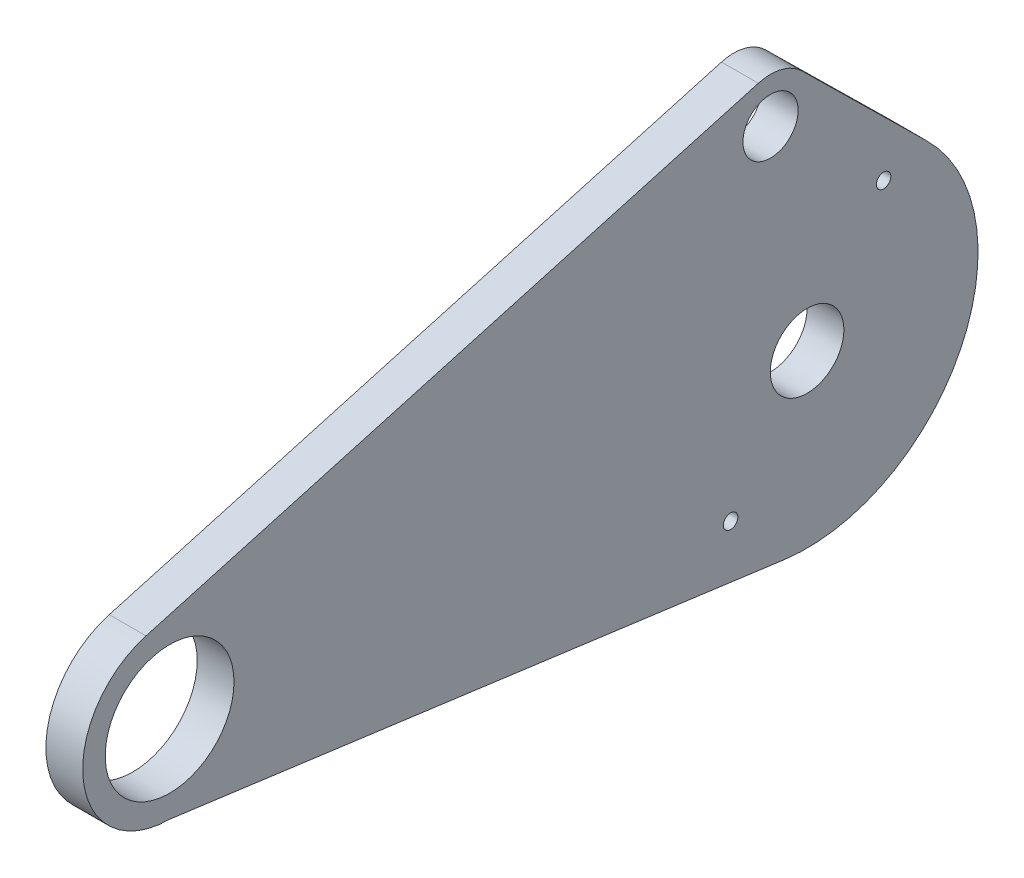
SolidWorks part; units mm, degrees
ref_plane "Front Plane" through (0, 0, 0) normal (0, 0, 1) x (1, 0, 0)
ref_plane "Top Plane" through (0, 0, 0) normal (0, 1, 0) x (1, 0, 0)
ref_plane "Right Plane" through (0, 0, 0) normal (1, 0, 0) x (0, 0, -1)
sketch "Sketch1" plane through (0, 0, 0) normal (1, 0, 0) x (0, 0, -1)
  line L4 (0, 15) -> (0, 11.1125) construction
  line L6 (0, 11.1125) -> (0, -11.1125) construction
  line L7 (0, -11.1125) -> (0, -15) construction
  line L8 (0, 15) -> (106.0756, 29.2378)
  line L9 (0, -15) -> (106.0756, -29.2378)
  line L10 (-4.0667, 14.4382) -> (101.5842, 44.1959)
  line L11 (130.6993, 21.0188) -> (109.1354, 42.2549)
  circle A0 centre (110, 0) radius 6.35
  circle A1 centre (0, 0) radius 11.1125
  arc A3 (106.0756, -29.2378) -> (106.0756, 29.2378) centre (110, 0) ccw
  arc A5 (0, 15) -> (0, -15) centre (0, 0) ccw
  arc A6 (106.0756, 29.2378) -> (106.0756, -29.2378) centre (110, 0) ccw construction
  arc A7 (0, -15) -> (0, 15) centre (0, 0) ccw construction
  circle A8 centre (0, 0) radius 110 construction
  circle A9 centre (0, 0) radius 100 construction
  circle A10 centre (103.6887, 36.7241) radius 4.7625
  circle A11 centre (103.6887, 36.7241) radius 7.7625
  dimension "D3" = 22.225
  dimension "D4" = 9.525
  dimension "D5" = 12.7
  dimension "D6" = 59
  dimension "D7" = 3
  dimension "D1" = 10
  dimension "D2" = 110
  dimension "D9" = 30
extrude "Boss-Extrude1" add sketch "Sketch1" along normal mid plane 6.35 contours A11 L8 A5 L9 A3 A0 A1 | A11 L10 A5 L8 | A11 L8 A3 L11 | A11 L8 A10 | L8 A11
hole_wizard "M3x0.5 Tapped Hole1" positions "Sketch2" profile "Sketch3" tap size "M3x0.5" standard "ANSI Metric" end condition through all
sketch "Sketch2" plane through (3.175, 0, 0) normal (1, 0, 0) x (0, 0, -1)
  line L0 (96.7991, -18.8528) -> (123.2009, 18.8528) construction
  line L2 (55, 0) -> (-55, 0) construction
  line L3 (0, 0) -> (110, 0) construction
  circle A1 centre (110, 0) radius 6.35 construction
  point P0 (123.2009, 18.8528)
  point P12 (110, 0)
  point P13 (96.7991, -18.8528)
  dimension "D1" = 23.015
  dimension "D2" = 125
sketch "Sketch3" plane through (3.175, 18.8528, -123.2009) normal (0, 1, 0) x (0, 0, -1)
  line L0 (0, 0) -> (0, 6.35)
  line L1 (0, 6.35) -> (1.25, 6.35)
  line L2 (1.25, 6.35) -> (1.25, 0)
  line L5 (1.25, 0) -> (0, 0)
  line L11 (0, -6.35) -> (0, 107.95) construction
  dimension "Thru Tap Drill Dia." = 2.5
  dimension "Thru Tap Drill Depth" = 6.35
cosmetic thread "Hole Thread1" parameters "D2"=3
cosmetic thread "Hole Thread2" parameters "D2"=3
hole_wizard "3/8 (0.3750) Dowel Hole1" positions "Sketch4" profile "Sketch5" hole size "3/8" standard "ANSI Inch"
sketch "Sketch4" plane through (3.175, 0, 0) normal (1, 0, 0) x (0, 0, -1)
  point P0 (65, 0)
  dimension "D1" = 65
sketch "Sketch5" plane through (3.175, 0, -65) normal (0, 1, 0) x (0, 0, -1)
  line L0 (0, 0) -> (0, 6.35)
  line L1 (0, 6.35) -> (4.7625, 6.35)
  line L2 (4.7625, 6.35) -> (4.7625, 0)
  line L5 (4.7625, 0) -> (0, 0)
  line L11 (0, -6.35) -> (0, 107.95) construction
  dimension "Thru Hole Dia." = 9.525
  dimension "Thru Hole Depth" = 6.35
